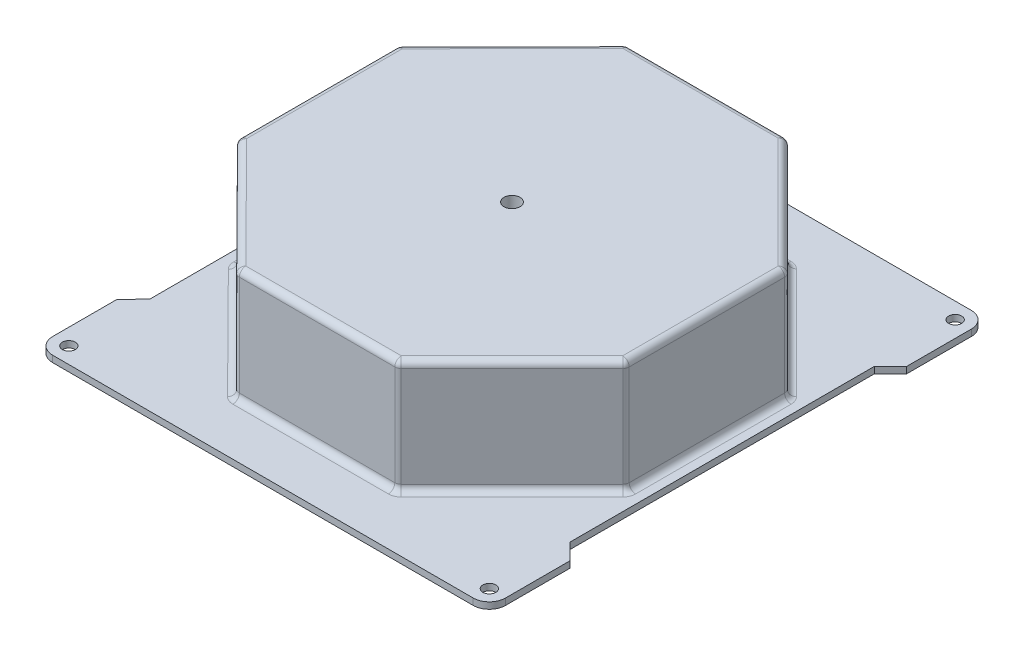
SolidWorks part; units mm, degrees
ref_plane "Front Plane" through (0, 0, 0) normal (0, 0, 1) x (1, 0, 0)
ref_plane "Top Plane" through (0, 0, 0) normal (0, 1, 0) x (1, 0, 0)
ref_plane "Right Plane" through (0, 0, 0) normal (1, 0, 0) x (0, 0, -1)
other "Center of Mass"
sketch "Sketch1" plane through (0, 0, 0) normal (0, 1, 0) x (1, 0, 0)
  line L0 (-65, 47) -> (-65, -47)
  line L1 (-65, 77) -> (65, 77)
  line L2 (-70, 72) -> (-70, 51.899)
  line L3 (-65, -77) -> (65, -77)
  line L4 (70, 72) -> (70, 51.899)
  line L5 (-70, 77) -> (70, -77) construction
  line L6 (-70, -77) -> (70, 77) construction
  line L7 (-70, -52.1031) -> (-70, -72)
  line L9 (-65, -47) -> (-70, -52.1031)
  line L10 (-65, 47) -> (-70, 51.899)
  line L11 (65, -47) -> (70, -52.1031)
  line L12 (65, 47) -> (70, 51.899)
  line L13 (65, 47) -> (65, -47)
  line L14 (70, -52.1031) -> (70, -72)
  arc A0 (-70, 72) -> (-65, 77) centre (-65, 72) cw
  arc A1 (70, 72) -> (65, 77) centre (65, 72) ccw
  arc A2 (70, -72) -> (65, -77) centre (65, -72) cw
  arc A3 (-70, -72) -> (-65, -77) centre (-65, -72) ccw
  circle A5 centre (-65, -72) radius 2
  circle A6 centre (65, -72) radius 2
  circle A7 centre (-65, 72) radius 2
  circle A8 centre (65, 72) radius 2
  point P0 (0, 0)
  dimension "D1" = 5
  dimension "D2" = 5
  dimension "D3" = 5
  dimension "D4" = 5
  dimension "D5" = 5
  dimension "D7" = 154
extrude "Boss-Extrude1" add sketch "Sketch1" along normal blind 2
sketch "Sketch2" plane through (0, 2, 0) normal (0, 1, 0) x (1, 0, 0)
  line L0 (-65, 47) -> (-65, -47) construction
  line L1 (65, 77) -> (-65, 77) construction
  line L2 (65, -47) -> (65, 47) construction
  line L3 (-65, -77) -> (65, -77) construction
  line L4 (-60, -24.8528) -> (-24.8528, -60.2623)
  line L5 (-24.8528, -60.2623) -> (24.8528, -60.2623)
  line L6 (24.8528, -60.2623) -> (60.2623, -24.8528)
  line L7 (60.2623, -24.8528) -> (60.2623, 24.8528)
  line L8 (24.8528, 60.2623) -> (60.2623, 24.8528)
  line L9 (-24.8528, 60.2623) -> (24.8528, 60.2623)
  line L10 (-60, 24.8528) -> (-24.8528, 60.2623)
  line L11 (-60, 24.8528) -> (-60, -24.8528)
  circle A0 centre (0, 0) radius 2.5
  point P4 (0, 0)
  point P8 (0, 0)
  point P11 (0, 0)
  point P12 (0, 0)
  point P15 (0, 0)
  point P18 (-42.4264, -42.5575)
  point P21 (0, -60.2623)
  point P24 (42.5575, -42.5575)
  point P27 (60.2623, 0)
  point P30 (42.5575, 42.5575)
  point P33 (0, 60.2623)
  point P36 (-42.4264, 42.5575)
  point P39 (-60, 0)
  dimension "D1" = 5
  dimension "D2" = 16.7377
  dimension "D3" = 4.7377
  dimension "D4" = 16.7377
  dimension "D5" = 135.213
  dimension "D6" = 135.213
  dimension "D7" = 225.213
  dimension "D8" = 225
  dimension "D9" = 135
  dimension "D10" = 135
  dimension "D11" = 49.7056
  dimension "D12" = 135
  dimension "D13" = 134.787
  dimension "D14" = 60.2623
extrude "Boss-Extrude2" add sketch "Sketch2" along normal blind 35
fillet "Fillet1" radius 2 24 edges at (0, 2, 60.2623) (42.5575, 2, 42.5575) (-42.4264, 2, 42.5575) (60.2623, 2, 0) (-60, 2, 0) (42.5575, 2, -42.5575) (-42.4264, 2, -42.5575) (0, 2, -60.2623) (42.5575, 37, -42.5575) (0, 37, -60.2623) (-42.4264, 37, -42.5575) (-60, 37, 0) (-60, 19.5, 24.8528) (-60, 19.5, -24.8528) (-24.8528, 19.5, -60.2623) (24.8528, 19.5, -60.2623) (60.2623, 19.5, -24.8528) (-42.4264, 37, 42.5575) (-24.8528, 19.5, 60.2623) (60.2623, 37, 0) (60.2623, 19.5, 24.8528) (42.5575, 37, 42.5575) (24.8528, 19.5, 60.2623) (0, 37, 60.2623)
